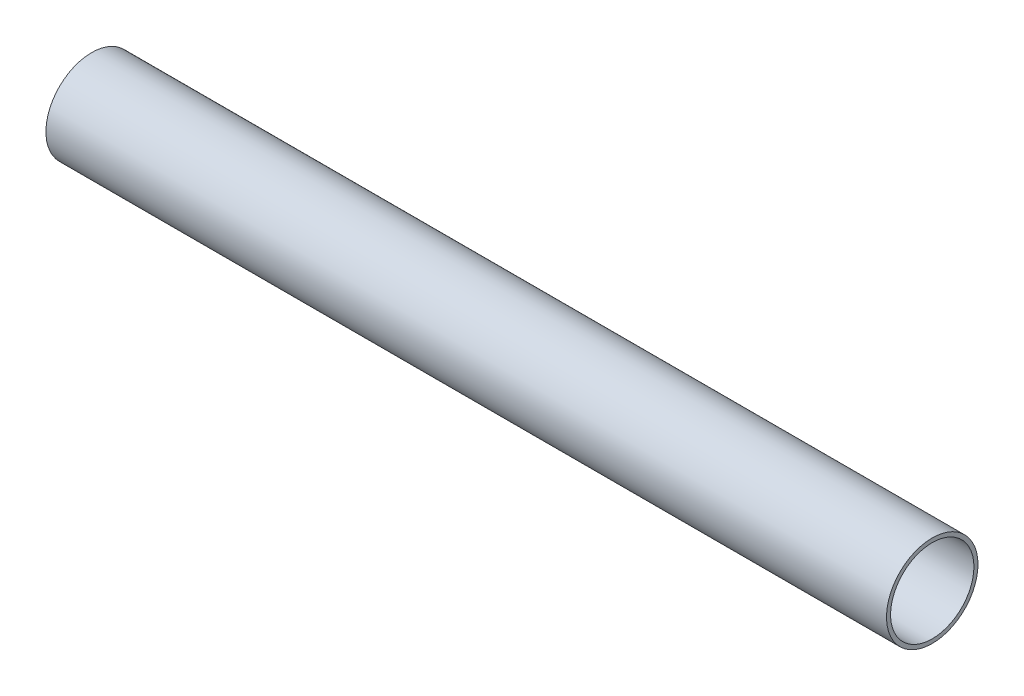
SolidWorks part; units mm, degrees
ref_plane "Vorne" through (0, 0, 0) normal (0, 0, 1) x (1, 0, 0)
ref_plane "Oben" through (0, 0, 0) normal (0, 1, 0) x (1, 0, 0)
ref_plane "Seite" through (0, 0, 0) normal (1, 0, 0) x (0, 0, -1)
sketch "Skizze1" plane through (0, 0, 0) normal (1, 0, 0) x (0, 0, -1)
  circle A0 centre (0, 0) radius 5.6
  circle A1 centre (0, 0) radius 5.1
  dimension "D1" = 10.2
  dimension "D2" = 11.2
extrude "Aufsatz-Linear austragen1" add sketch "Skizze1" along normal mid plane 102.9
